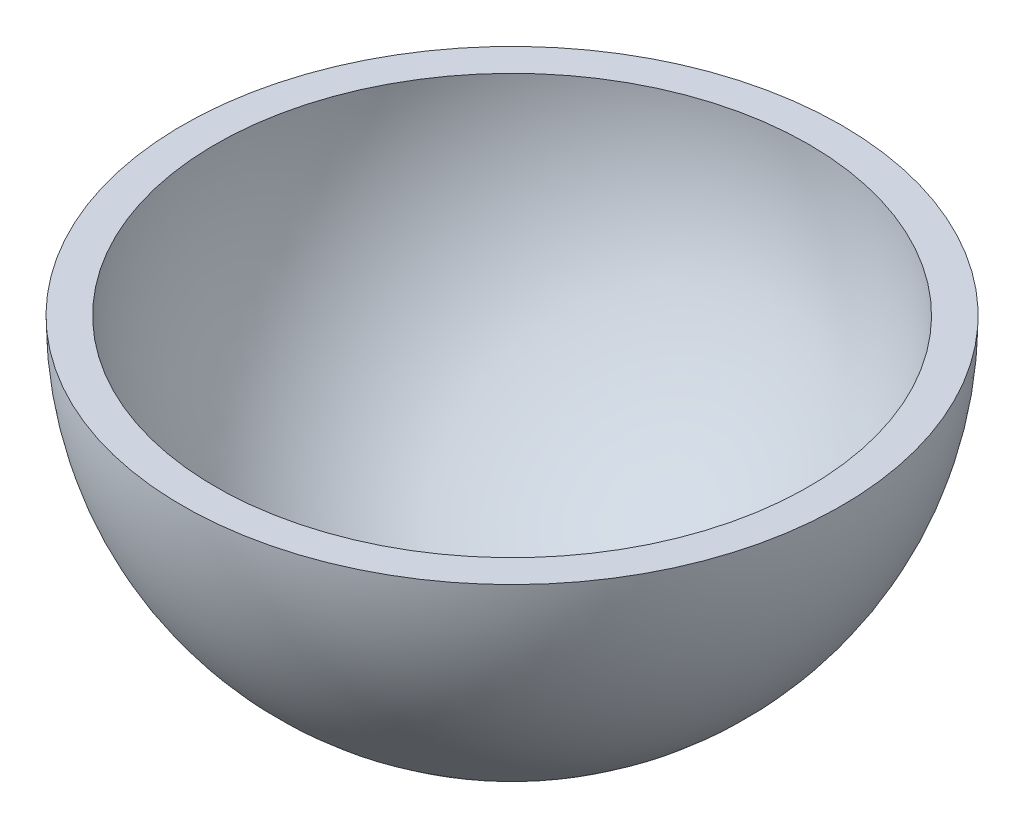
SolidWorks part; units mm, degrees
ref_plane "前视基准面" through (0, 0, 0) normal (0, 0, 1) x (1, 0, 0)
ref_plane "上视基准面" through (0, 0, 0) normal (0, 1, 0) x (1, 0, 0)
ref_plane "右视基准面" through (0, 0, 0) normal (1, 0, 0) x (0, 0, -1)
other "Configuration Table"
sketch "草图1" plane through (0, 0, 0) normal (0, 1, 0) x (1, 0, 0)
  line L0 (25, 0) -> (-25, 0) construction
  line L1 (-25, 0) -> (-22.5, 0)
  line L2 (22.5, 0) -> (25, 0)
  arc A0 (25, 0) -> (-25, 0) centre (0, 0) ccw
  arc A1 (22.5, 0) -> (-22.5, 0) centre (0, 0) ccw
  dimension "D1" = 50
  dimension "D3" = 2.5
revolve "旋转1" add sketch "草图1" angle 180 about L0
